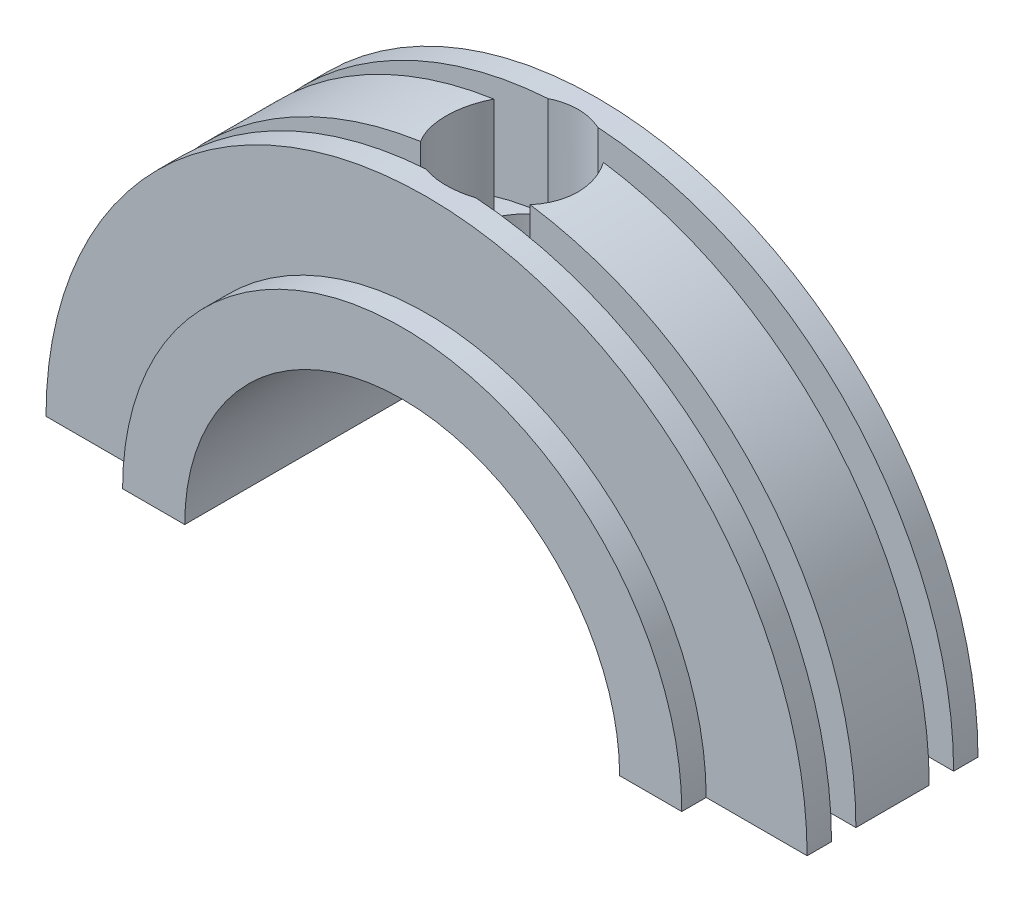
SolidWorks part; units mm, degrees
ref_plane "Front Plane" through (0, 0, 0) normal (0, 0, 1) x (1, 0, 0)
ref_plane "Top Plane" through (0, 0, 0) normal (0, 1, 0) x (1, 0, 0)
ref_plane "Right Plane" through (0, 0, 0) normal (1, 0, 0) x (0, 0, -1)
sketch "Sketch1" plane through (0, 0, 0) normal (0, 1, 0) x (1, 0, 0)
  line L0 (-14, -7.07) -> (-14, 7.07)
  line L1 (-14, 7.07) -> (-18, 7.07)
  line L2 (-18, 7.07) -> (-18, 5.5)
  line L3 (-18, 5.5) -> (-24.5, 5.5)
  line L4 (-24.5, 5.5) -> (-24.5, 3.93)
  line L5 (-24.5, 3.93) -> (-18, 3.93)
  line L6 (-18, 3.93) -> (-18, 2.36)
  line L7 (-18, 2.36) -> (-24.5, 2.36)
  line L8 (-24.5, 2.36) -> (-24.5, -2.36)
  line L9 (-24.5, -2.36) -> (-18, -2.36)
  line L10 (-18, -2.36) -> (-18, -3.93)
  line L11 (-18, -3.93) -> (-24.5, -3.93)
  line L12 (-24.5, -3.93) -> (-24.5, -5.5)
  line L13 (-24.5, -5.5) -> (-18, -5.5)
  line L14 (-18, -5.5) -> (-18, -7.07)
  line L15 (-18, -7.07) -> (-14, -7.07)
  line L16 (0, 0) -> (0, 7.0905) construction
  point P3 (-14, 0)
  point P20 (0, 0)
  dimension "D8" = 11
  dimension "D1" = 14
  dimension "D2" = 24.5
  dimension "D3" = 18
  dimension "D4" = 1.57
  dimension "D5" = 3.14
  dimension "D6" = 4.71
  dimension "D7" = 9.43
  dimension "D9" = 12.57
  dimension "D10" = 14.14
revolve "Revolve1" add sketch "Sketch1" angle 360 about L16
sketch "Sketch3" plane through (0, 0, 0) normal (0, 0, 1) x (1, 0, 0)
  line L0 (-24.5, 0) -> (24.5, 0)
  circle A0 centre (0, 0) radius 24.5 construction
  circle A1 centre (0, 0) radius 14 construction
  arc A2 (-14, 0) -> (14, 0) centre (0, 0) ccw
  arc A3 (-24.5, 0) -> (24.5, 0) centre (0, 0) ccw
extrude "Cut-Extrude1" cut sketch "Sketch3" against normal through all both and the other way through all contours L0 A3 A2
sketch "Sketch4" plane through (0, 0, 0) normal (0, 1, 0) x (1, 0, 0)
  circle A0 centre (0, 0) radius 4.245
  dimension "D1" = 8.49
extrude "Cut-Extrude2" cut sketch "Sketch4" along normal through all both
sketch "Sketch5" plane through (0, 0, 0) normal (0, -1, 0) x (1, 0, 0)
  line L0 (-24.5, -2.36) -> (-18, -2.36) construction
  circle A0 centre (-21.25, 0) radius 1.1
  point P4 (-21.25, -2.36)
  dimension "D1" = 2.2
hole_wizard "Tap Drill for M2x0.4 Tap1" positions "3DSketch1" profile "Sketch6" hole size "M2x0.4" standard "ANSI Metric"
sketch3d "3DSketch1"
  point P0 (-21.25, 0, 0)
sketch "Sketch6" plane through (-21.25, 0, 0) normal (1, 0, 0) x (0, 0, -1)
  line L0 (0, 0) -> (0, 7.2)
  line L1 (0, 7.2) -> (1.1, 6.5649)
  line L2 (1.1, 6.5649) -> (1.1, 0)
  line L5 (1.1, 0) -> (0, 0)
  line L10 (0, 7.2) -> (-1.1, 6.5649) construction
  line L11 (0, -6.35) -> (0, 107.95) construction
  dimension "Hole Dia." = 2.2
  dimension "Hole Depth" = 7.2
  dimension "Drill Angle" = 120
mirror "Mirror1" about plane through (0, 0, 0) normal (1, 0, 0) of "Tap Drill for M2x0.4 Tap1"
